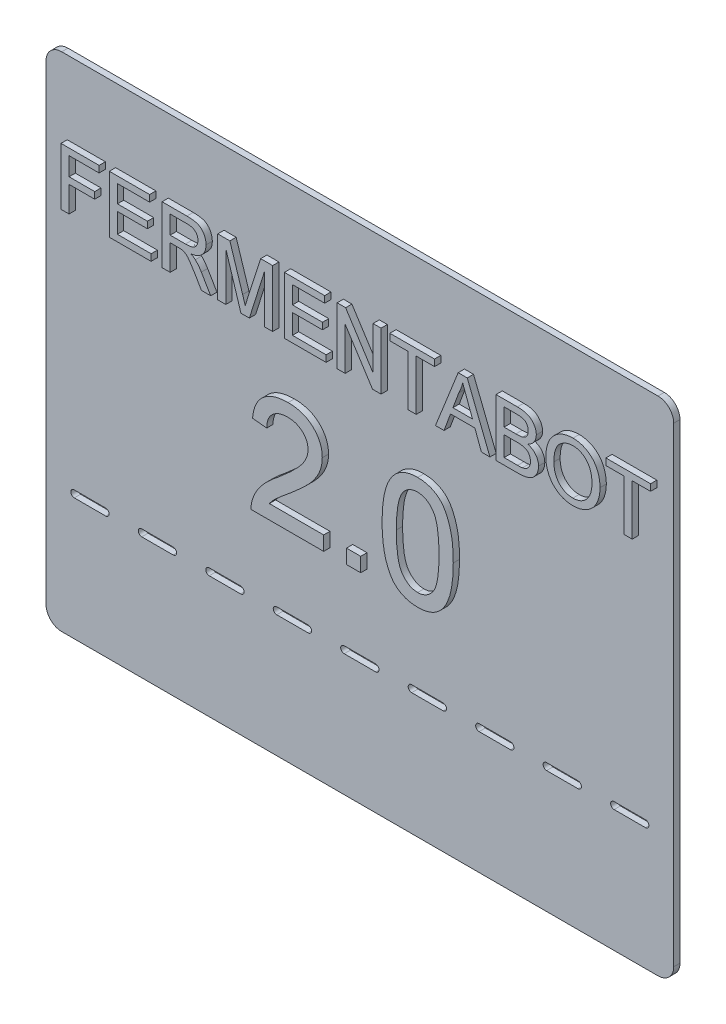
SolidWorks part; units mm, degrees
ref_plane "Front" through (0, 0, 0) normal (0, 0, 1) x (1, 0, 0)
ref_plane "Top" through (0, 0, 0) normal (0, 1, 0) x (1, 0, 0)
ref_plane "Right" through (0, 0, 0) normal (1, 0, 0) x (0, 0, -1)
sketch "Sketch1" plane through (0, 0, 0) normal (0, 0, 1) x (1, 0, 0)
  line L0 (-127, -50.8) -> (127, -50.8) construction
  line L1 (-127, 101.6) -> (127, 101.6) construction
  line L2 (-127, 101.6) -> (-127, -101.6) construction
  line L3 (-127, -101.6) -> (127, -101.6) construction
  line L4 (127, 101.6) -> (127, -101.6) construction
  line L5 (-127, 101.6) -> (127, -101.6) construction
  line L6 (-127, -101.6) -> (127, 101.6) construction
  line L7 (0, 0) -> (0, -50.8) construction
  line L8 (-6.35, -50.8) -> (6.35, -50.8) construction
  line L9 (-6.35, -49.403) -> (6.35, -49.403) construction
  line L10 (-6.35, -52.197) -> (6.35, -52.197) construction
  line L11 (-127, 48.7768) -> (127, 48.7768) construction
  line L12 (-127, -17.9454) -> (127, -17.9454) construction
  arc A0 (-6.35, -49.403) -> (-6.35, -52.197) centre (-6.35, -50.8) ccw construction
  arc A1 (6.35, -52.197) -> (6.35, -49.403) centre (6.35, -50.8) ccw construction
  text T0 "FERMENTABOT" font "Arial" height in points 90
  text T1 "2.0" font "Arial" height in points 175
  point P0 (0, 0)
  point P12 (0, -50.8)
  dimension "D1" = 254
  dimension "D2" = 152.4
  dimension "D3" = 50.8
  dimension "D4" = 2.794
  dimension "D5" = 12.7
extrude "Boss-Extrude2" add sketch "Sketch1" along normal blind 2.54
sketch "Sketch3" plane through (0, 0, 0) normal (0, 0, -1) x (-1, 0, 0)
  line L0 (127, -101.6) -> (-127, -101.6) construction
  line L1 (-127, 101.6) -> (-127, -101.6) construction
  line L2 (127, 101.6) -> (-127, 101.6) construction
  line L3 (127, 101.6) -> (127, -101.6) construction
  line L4 (127, -101.6) -> (-127, -101.6)
  line L5 (-127, 101.6) -> (-127, -101.6)
  line L6 (127, 101.6) -> (-127, 101.6)
  line L7 (127, 101.6) -> (127, -101.6)
extrude "Boss-Extrude3" add sketch "Sketch3" along normal blind 2.54
sketch "Sketch4" plane through (0, 0, 0) normal (0, 0, 1) x (1, 0, 0)
  line L0 (-6.35, -52.197) -> (6.35, -52.197) construction
  line L1 (-6.35, -52.197) -> (6.35, -52.197)
  line L2 (-6.35, -49.403) -> (6.35, -49.403) construction
  line L3 (-6.35, -49.403) -> (6.35, -49.403)
  arc A0 (6.35, -52.197) -> (6.35, -49.403) centre (6.35, -50.8) ccw construction
  arc A1 (-6.35, -49.403) -> (-6.35, -52.197) centre (-6.35, -50.8) ccw construction
  arc A2 (6.35, -52.197) -> (6.35, -49.403) centre (6.35, -50.8) ccw
  arc A3 (-6.35, -49.403) -> (-6.35, -52.197) centre (-6.35, -50.8) ccw
extrude "Cut-Extrude1" cut sketch "Sketch4" against normal through all
pattern_linear "LPattern1" count 5 spacing 27.305 along (1, 0, 0) of "Cut-Extrude1"
pattern_linear "LPattern2" count 5 spacing 27.305 along (-1, 0, 0) of "Cut-Extrude1"
fillet "Fillet1" radius 6.35 4 edges at (-127, -101.6, -1.27) (127, -101.6, -1.27) (127, 101.6, -1.27) (-127, 101.6, -1.27)
